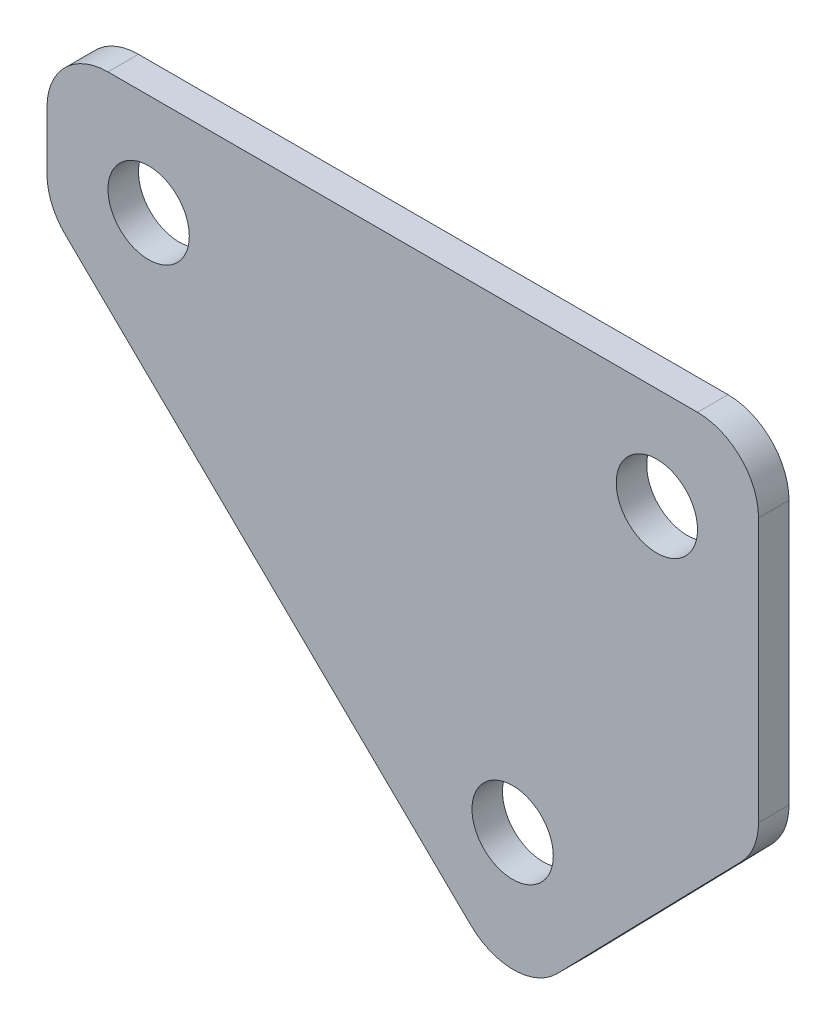
SolidWorks part; units mm, degrees
material "1060 合金"
ref_plane "正面" through (0, 0, 0) normal (0, 0, 1) x (1, 0, 0)
ref_plane "平面" through (0, 0, 0) normal (0, 1, 0) x (1, 0, 0)
ref_plane "右側面" through (0, 0, 0) normal (1, 0, 0) x (0, 0, -1)
sketch "ｽｹｯﾁ1" plane through (0, 0, 0) normal (0, 0, 1) x (1, 0, 0)
  line L0 (-17.5, 9.7592) -> (17.5, 9.7592) construction
  line L1 (-17.5, -14.7592) -> (17.5, -14.7592)
  line L2 (-17.5, -14.7592) -> (-17.5, 14.7592)
  line L3 (-17.5, 14.7592) -> (17.5, 14.7592)
  line L4 (17.5, -14.7592) -> (17.5, 14.7592)
  line L5 (-17.5, -14.7592) -> (17.5, 14.7592) construction
  line L6 (-17.5, 14.7592) -> (17.5, -14.7592) construction
  line L7 (0, 14.7592) -> (0, -14.7592) construction
  line L8 (-12.5, 9.7592) -> (5.4045, -7.6887) construction
  line L9 (-17.5, 7.6502) -> (5.4958, -14.7592)
  line L10 (5.4958, -14.7592) -> (17.5, -2.4409)
  circle A0 centre (-12.5, 9.7592) radius 2
  circle A1 centre (12.5, 9.7592) radius 2
  circle A2 centre (5.4045, -7.6887) radius 2
  point P0 (0, 0)
  dimension "D1" = 25
  dimension "D2" = 5
  dimension "D3" = 5
  dimension "D6" = 4
  dimension "D7" = 5
  dimension "D9" = 5
  dimension "D8" = 5
  dimension "D4" = 135.74
  dimension "D5" = 25
extrude "ﾎﾞｽ - 押し出し1" add sketch "ｽｹｯﾁ1" along normal blind 1.5 contours L9 L10 L4 L3 L2 A2 A0 A1
fillet "ﾌｨﾚｯﾄ1" radius 3 5 edges at (17.5, 14.7592, 0.75) (17.5, -2.4409, 0.75) (5.4958, -14.7592, 0.75) (-17.5, 7.6502, 0.75) (-17.5, 14.7592, 0.75)
